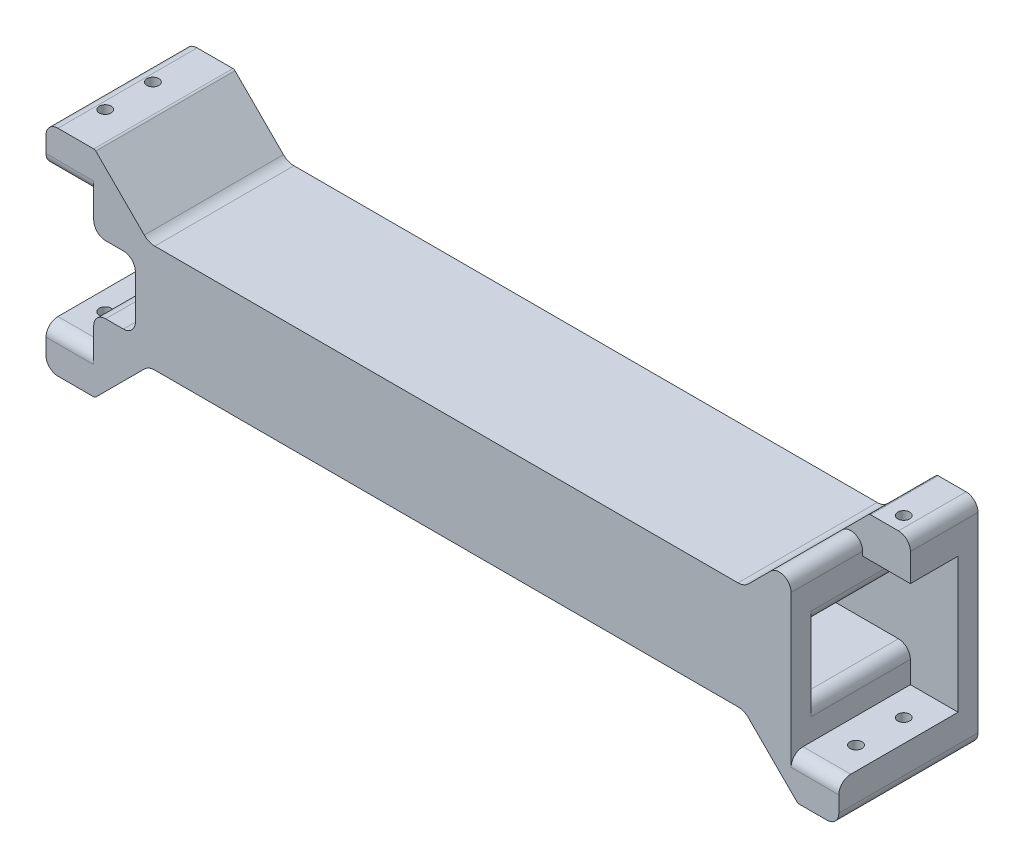
SolidWorks part; units mm, degrees
ref_plane "前视基准面" through (0, 0, 0) normal (0, 0, 1) x (1, 0, 0)
ref_plane "上视基准面" through (0, 0, 0) normal (0, 1, 0) x (1, 0, 0)
ref_plane "右视基准面" through (0, 0, 0) normal (1, 0, 0) x (0, 0, -1)
other "Configuration Table"
sketch "草图1" plane through (0, 0, 0) normal (0, 0, 1) x (1, 0, 0)
  line L0 (49.1217, 60) -> (0, 60) construction
  line L1 (0, 60) -> (0, 57) construction
  line L2 (0, 57) -> (49.1217, 57) construction
  line L3 (63.9537, 46.7157) -> (51.7639, 58.9056) construction
  line L4 (49.6425, 56.7843) -> (61.8324, 44.5944) construction
  line L5 (49.1217, 3) -> (0, 3) construction
  line L6 (0, 3) -> (0, 0) construction
  line L7 (0, 0) -> (49.1217, 0) construction
  line L8 (61.8324, 15.4056) -> (49.6425, 3.2157) construction
  line L9 (51.7639, 1.0944) -> (63.9537, 13.2843) construction
  line L10 (64.4745, 43.5) -> (211.1217, 43.5) construction
  line L11 (211.1217, 46.5) -> (64.4745, 46.5) construction
  line L12 (213.7639, 44.5944) -> (225.9537, 56.7843) construction
  line L13 (223.8324, 58.9056) -> (211.6425, 46.7157) construction
  line L14 (226.4745, 57) -> (269.9745, 57) construction
  line L15 (269.9745, 57) -> (269.9745, 60) construction
  line L16 (269.9745, 60) -> (226.4745, 60) construction
  line L17 (64.4745, 13.5) -> (211.1217, 13.5) construction
  line L18 (211.1217, 16.5) -> (64.4745, 16.5) construction
  line L19 (211.6425, 13.2843) -> (223.8324, 1.0944) construction
  line L20 (225.9537, 3.2157) -> (213.7639, 15.4056) construction
  line L21 (226.4745, 0) -> (269.9745, 0) construction
  line L22 (269.9745, 0) -> (269.9745, 3) construction
  line L23 (269.9745, 3) -> (226.4745, 3) construction
  line L24 (49.1217, 60) -> (0, 60)
  line L25 (0, 60) -> (0, 57)
  line L26 (0, 57) -> (49.1217, 57)
  line L27 (63.9537, 46.7157) -> (51.7639, 58.9056)
  line L28 (49.6425, 56.7843) -> (61.8324, 44.5944)
  line L29 (49.1217, 3) -> (0, 3)
  line L30 (0, 3) -> (0, 0)
  line L31 (0, 0) -> (49.1217, 0)
  line L32 (61.8324, 15.4056) -> (49.6425, 3.2157)
  line L33 (51.7639, 1.0944) -> (63.9537, 13.2843)
  line L34 (64.4745, 43.5) -> (211.1217, 43.5)
  line L35 (211.1217, 46.5) -> (64.4745, 46.5)
  line L36 (213.7639, 44.5944) -> (225.9537, 56.7843)
  line L37 (223.8324, 58.9056) -> (211.6425, 46.7157)
  line L38 (226.4745, 57) -> (269.9745, 57)
  line L39 (269.9745, 57) -> (269.9745, 60)
  line L40 (269.9745, 60) -> (226.4745, 60)
  line L41 (64.4745, 13.5) -> (211.1217, 13.5)
  line L42 (211.1217, 16.5) -> (64.4745, 16.5)
  line L43 (211.6425, 13.2843) -> (223.8324, 1.0944)
  line L44 (225.9537, 3.2157) -> (213.7639, 15.4056)
  line L45 (226.4745, 0) -> (269.9745, 0)
  line L46 (269.9745, 0) -> (269.9745, 3)
  line L47 (269.9745, 3) -> (226.4745, 3)
  line L48 (236.4745, 3) -> (236.4745, 57)
  line L49 (37.1217, 3) -> (37.1217, 57)
  arc A0 (49.6425, 56.7843) -> (49.1217, 57) centre (49.1217, 56.2634) ccw construction
  arc A1 (51.7639, 58.9056) -> (49.1217, 60) centre (49.1217, 56.2634) ccw construction
  arc A2 (61.8324, 44.5944) -> (64.4745, 43.5) centre (64.4745, 47.2366) ccw construction
  arc A3 (63.9537, 46.7157) -> (64.4745, 46.5) centre (64.4745, 47.2366) ccw construction
  arc A4 (49.1217, 0) -> (51.7639, 1.0944) centre (49.1217, 3.7366) ccw construction
  arc A5 (49.1217, 3) -> (49.6425, 3.2157) centre (49.1217, 3.7366) ccw construction
  arc A6 (64.4745, 13.5) -> (63.9537, 13.2843) centre (64.4745, 12.7634) ccw construction
  arc A7 (64.4745, 16.5) -> (61.8324, 15.4056) centre (64.4745, 12.7634) ccw construction
  arc A8 (211.1217, 43.5) -> (213.7639, 44.5944) centre (211.1217, 47.2366) ccw construction
  arc A9 (211.1217, 46.5) -> (211.6425, 46.7157) centre (211.1217, 47.2366) ccw construction
  arc A10 (226.4745, 57) -> (225.9537, 56.7843) centre (226.4745, 56.2634) ccw construction
  arc A11 (226.4745, 60) -> (223.8324, 58.9056) centre (226.4745, 56.2634) ccw construction
  arc A12 (211.6425, 13.2843) -> (211.1217, 13.5) centre (211.1217, 12.7634) ccw construction
  arc A13 (213.7639, 15.4056) -> (211.1217, 16.5) centre (211.1217, 12.7634) ccw construction
  arc A14 (223.8324, 1.0944) -> (226.4745, 0) centre (226.4745, 3.7366) ccw construction
  arc A15 (225.9537, 3.2157) -> (226.4745, 3) centre (226.4745, 3.7366) ccw construction
  arc A16 (49.6425, 56.7843) -> (49.1217, 57) centre (49.1217, 56.2634) ccw
  arc A17 (51.7639, 58.9056) -> (49.1217, 60) centre (49.1217, 56.2634) ccw
  arc A18 (61.8324, 44.5944) -> (64.4745, 43.5) centre (64.4745, 47.2366) ccw
  arc A19 (63.9537, 46.7157) -> (64.4745, 46.5) centre (64.4745, 47.2366) ccw
  arc A20 (49.1217, 0) -> (51.7639, 1.0944) centre (49.1217, 3.7366) ccw
  arc A21 (49.1217, 3) -> (49.6425, 3.2157) centre (49.1217, 3.7366) ccw
  arc A22 (64.4745, 13.5) -> (63.9537, 13.2843) centre (64.4745, 12.7634) ccw
  arc A23 (64.4745, 16.5) -> (61.8324, 15.4056) centre (64.4745, 12.7634) ccw
  arc A24 (211.1217, 43.5) -> (213.7639, 44.5944) centre (211.1217, 47.2366) ccw
  arc A25 (211.1217, 46.5) -> (211.6425, 46.7157) centre (211.1217, 47.2366) ccw
  arc A26 (226.4745, 57) -> (225.9537, 56.7843) centre (226.4745, 56.2634) ccw
  arc A27 (226.4745, 60) -> (223.8324, 58.9056) centre (226.4745, 56.2634) ccw
  arc A28 (211.6425, 13.2843) -> (211.1217, 13.5) centre (211.1217, 12.7634) ccw
  arc A29 (213.7639, 15.4056) -> (211.1217, 16.5) centre (211.1217, 12.7634) ccw
  arc A30 (223.8324, 1.0944) -> (226.4745, 0) centre (226.4745, 3.7366) ccw
  arc A31 (225.9537, 3.2157) -> (226.4745, 3) centre (226.4745, 3.7366) ccw
  dimension "D1" = 10
  dimension "D2" = 12
extrude "凸台-拉伸1" add sketch "草图1" against normal blind 35 contours L44 A31 L47 L48 L38 A26 L36 A24 L34 A18 L28 A16 L26 L49 L29 A21 L32 A23 L42 A29
sketch "草图2" plane through (37.1217, 0, 0) normal (-1, 0, 0) x (0, 0, 1)
  line L0 (-35, 43.5) -> (0, 43.5) construction
  line L1 (-35, 43.5) -> (0, 43.5)
  line L2 (-35, 16.5) -> (0, 16.5) construction
  line L3 (-35, 16.5) -> (0, 16.5)
  line L4 (-35, 43.5) -> (0, 16.5) construction
  line L5 (-35, 16.5) -> (0, 43.5) construction
  line L6 (0, 3) -> (0, 57) construction
  line L7 (-30, 38.5) -> (-5, 38.5)
  line L8 (-30, 38.5) -> (-30, 21.5)
  line L9 (-30, 21.5) -> (-5, 21.5)
  line L10 (-5, 38.5) -> (-5, 21.5)
  line L11 (-30, 38.5) -> (-5, 21.5) construction
  line L12 (-30, 21.5) -> (-5, 38.5) construction
  point P4 (-17.5, 30)
  dimension "D1" = 5
  dimension "D2" = 5
extrude "切除-拉伸1" cut sketch "草图2" against normal through all contours L10 L7 L8 L9
sketch "草图3" plane through (37.1217, 0, 0) normal (-1, 0, 0) x (0, 0, 1)
  line L0 (-30, 52) -> (-30, 8)
  line L1 (-30, 8) -> (-5, 8)
  line L2 (-5, 8) -> (-5, 52)
  line L3 (-5, 52) -> (-30, 52)
  line L4 (0, 3) -> (0, 57)
  line L5 (0, 57) -> (-35, 57)
  line L6 (-35, 57) -> (-35, 3)
  line L7 (-35, 3) -> (0, 3)
  line L8 (0, 3) -> (0, 57)
  line L9 (0, 57) -> (-35, 57)
  line L10 (-35, 57) -> (-35, 3)
  line L11 (-35, 3) -> (0, 3)
  line L12 (-30, 47) -> (-5, 47)
  line L13 (-30, 13) -> (-5, 13)
  line M14 (-5, 21.5) -> (-30, 21.5)
  line M16 (-30, 38.5) -> (-5, 38.5)
  dimension "D3" = 5
  dimension "D4" = 5
  dimension "D1" = 0
  dimension "D2" = 5
extrude "切除-拉伸2" cut sketch "草图3" against normal blind 12 contours L12 L0 L2 M16 | L0 L13 L2 M14
ref_plane "基准面1" through (136.7981, 0, 0) normal (-1, 0, 0) x (0, 0, 1)
mirror "镜向1" about plane through (136.7981, 0, 0) normal (-1, 0, 0) of "切除-拉伸2"
fillet "圆角1" radius 3 8 edges at (224.4745, 38.5, -17.5) (224.4745, 21.5, -17.5) (236.4745, 57, -17.5) (236.4745, 3, -17.5) (37.1217, 57, -17.5) (37.1217, 3, -17.5) (49.1217, 21.5, -17.5) (49.1217, 38.5, -17.5)
sketch "草图4" plane through (0, 57, 0) normal (0, 1, 0) x (1, 0, 0)
  circle A2 centre (42, 22) radius 1.5 construction
  circle A3 centre (42, 10) radius 1.5 construction
  circle A6 centre (42, 22) radius 1.5
  circle A7 centre (42, 10) radius 1.5
  circle A8 centre (230.7981, 22) radius 1.5 construction
  circle A9 centre (230.7981, 10) radius 1.5 construction
  circle A10 centre (230.7981, 22) radius 1.5
  circle A11 centre (230.7981, 10) radius 1.5
extrude "切除-拉伸3" cut sketch "草图4" against normal through all both and the other way through all
sketch "草图5" plane through (0, 0, -5) normal (0, 0, -1) x (-1, 0, 0)
  line L0 (-224.4745, 41.5) -> (-224.4745, 18.5)
  line L1 (-49.1217, 41.5) -> (-49.1217, 18.5)
  line L12 (-37.1217, 13) -> (-37.1217, 47)
  line L13 (-37.1217, 47) -> (-49.1217, 47)
  line L14 (-49.1217, 47) -> (-49.1217, 41.5)
  line L15 (-52.1217, 38.5) -> (-221.4745, 38.5)
  line L16 (-224.4745, 41.5) -> (-224.4745, 47)
  line L17 (-224.4745, 47) -> (-236.4745, 47)
  line L18 (-236.4745, 47) -> (-236.4745, 13)
  line L19 (-236.4745, 13) -> (-224.4745, 13)
  line L20 (-224.4745, 13) -> (-224.4745, 18.5)
  line L21 (-221.4745, 21.5) -> (-52.1217, 21.5)
  line L22 (-49.1217, 18.5) -> (-49.1217, 13)
  line L23 (-49.1217, 13) -> (-37.1217, 13)
  line L24 (-37.1217, 13) -> (-37.1217, 47)
  line L25 (-37.1217, 47) -> (-49.1217, 47)
  line L26 (-49.1217, 47) -> (-49.1217, 41.5)
  line L27 (-52.1217, 38.5) -> (-221.4745, 38.5)
  line L28 (-224.4745, 41.5) -> (-224.4745, 47)
  line L29 (-224.4745, 47) -> (-236.4745, 47)
  line L30 (-236.4745, 47) -> (-236.4745, 13)
  line L31 (-236.4745, 13) -> (-224.4745, 13)
  line L32 (-224.4745, 13) -> (-224.4745, 18.5)
  line L33 (-221.4745, 21.5) -> (-52.1217, 21.5)
  line L34 (-49.1217, 18.5) -> (-49.1217, 13)
  line L35 (-49.1217, 13) -> (-37.1217, 13)
  arc A4 (-52.1217, 38.5) -> (-49.1217, 41.5) centre (-52.1217, 41.5) ccw
  arc A5 (-224.4745, 41.5) -> (-221.4745, 38.5) centre (-221.4745, 41.5) ccw
  arc A6 (-221.4745, 21.5) -> (-224.4745, 18.5) centre (-221.4745, 18.5) ccw
  arc A7 (-49.1217, 18.5) -> (-52.1217, 21.5) centre (-52.1217, 18.5) ccw
  arc A8 (-52.1217, 38.5) -> (-49.1217, 41.5) centre (-52.1217, 41.5) ccw
  arc A9 (-224.4745, 41.5) -> (-221.4745, 38.5) centre (-221.4745, 41.5) ccw
  arc A10 (-221.4745, 21.5) -> (-224.4745, 18.5) centre (-221.4745, 18.5) ccw
  arc A11 (-49.1217, 18.5) -> (-52.1217, 21.5) centre (-52.1217, 18.5) ccw
  line M17 (-37.1217, 13) -> (-37.1217, 47)
  line M18 (-37.1217, 47) -> (-49.1217, 47)
  line M19 (-49.1217, 47) -> (-49.1217, 41.5)
  line M23 (-224.4745, 41.5) -> (-224.4745, 47)
  line M24 (-224.4745, 47) -> (-236.4745, 47)
  line M25 (-236.4745, 47) -> (-236.4745, 13)
  line M26 (-236.4745, 13) -> (-224.4745, 13)
  line M27 (-224.4745, 13) -> (-224.4745, 18.5)
  line M31 (-49.1217, 18.5) -> (-49.1217, 13)
  line M32 (-49.1217, 13) -> (-37.1217, 13)
  dimension "D1" = 0
extrude "切除-拉伸4" cut sketch "草图5" against normal blind 10 contours L0 M23 M24 M25 M26 M27 | L1 M19 M31 M32 M17 M18
fillet "圆角2" radius 3 4 edges at (230.4745, 13, 0) (230.4745, 47, 0) (43.1217, 13, 0) (43.1217, 47, 0)
sketch "草图6" plane through (0, 16.5, 0) normal (0, -1, 0) x (1, 0, 0)
  line L0 (106.7981, -17.5) -> (166.7981, -17.5) construction
  line L1 (136.7981, 19.25) -> (136.7981, -19.25) construction
  line L2 (106.7981, -9.5) -> (166.7981, -9.5)
  line L3 (106.7981, -25.5) -> (166.7981, -25.5)
  line L4 (136.7981, 0) -> (136.7981, -35)
  line L5 (211.1217, 0) -> (64.4745, 0) construction
  line L6 (211.1217, -35) -> (64.4745, -35) construction
  arc A0 (106.7981, -9.5) -> (106.7981, -25.5) centre (106.7981, -17.5) ccw
  arc A1 (166.7981, -25.5) -> (166.7981, -9.5) centre (166.7981, -17.5) ccw
  point P4 (136.7981, -17.5)
  dimension "D2" = 8
  dimension "D1" = 60
extrude "切除-拉伸5" [suppressed] cut sketch "草图6" against normal through all
sketch "草图7" plane through (0, 0, 0) normal (0, 0, 1) x (1, 0, 0)
  line L0 (236.4745, 47) -> (236.4745, 50) construction
  line L1 (224.4745, 47) -> (224.4745, 50) construction
  line L2 (224.4745, 47) -> (236.4745, 47) construction
  line L3 (49.1217, 50) -> (49.1217, 10) construction
  line L4 (49.1217, 10) -> (37.1217, 10) construction
  line L5 (37.1217, 10) -> (37.1217, 6) construction
  line L6 (40.1217, 3) -> (49.1217, 3) construction
  line L7 (49.6425, 3.2157) -> (61.8324, 15.4056) construction
  line L8 (64.4745, 16.5) -> (211.1217, 16.5) construction
  line L9 (213.7639, 15.4056) -> (225.9537, 3.2157) construction
  line L10 (226.4745, 3) -> (233.4745, 3) construction
  line L11 (236.4745, 6) -> (236.4745, 10) construction
  line L12 (236.4745, 10) -> (224.4745, 10) construction
  line L13 (224.4745, 10) -> (224.4745, 50) construction
  line L14 (236.4745, 50) -> (236.4745, 54) construction
  line L15 (233.4745, 57) -> (226.4745, 57) construction
  line L16 (225.9537, 56.7843) -> (213.7639, 44.5944) construction
  line L17 (211.1217, 43.5) -> (64.4745, 43.5) construction
  line L18 (61.8324, 44.5944) -> (49.6425, 56.7843) construction
  line L19 (49.1217, 57) -> (40.1217, 57) construction
  line L20 (37.1217, 54) -> (37.1217, 50) construction
  line L21 (37.1217, 50) -> (49.1217, 50) construction
  line L22 (236.4745, 47) -> (236.4745, 50)
  line L23 (224.4745, 47) -> (224.4745, 50)
  line L24 (224.4745, 47) -> (236.4745, 47)
  line L25 (49.1217, 50) -> (49.1217, 10)
  line L26 (49.1217, 10) -> (37.1217, 10)
  line L27 (37.1217, 10) -> (37.1217, 6)
  line L28 (40.1217, 3) -> (49.1217, 3)
  line L29 (49.6425, 3.2157) -> (61.8324, 15.4056)
  line L30 (64.4745, 16.5) -> (211.1217, 16.5)
  line L31 (213.7639, 15.4056) -> (225.9537, 3.2157)
  line L32 (226.4745, 3) -> (233.4745, 3)
  line L33 (236.4745, 6) -> (236.4745, 10)
  line L34 (236.4745, 10) -> (224.4745, 10)
  line L35 (224.4745, 10) -> (224.4745, 50)
  line L36 (236.4745, 50) -> (236.4745, 54)
  line L37 (233.4745, 57) -> (226.4745, 57)
  line L38 (225.9537, 56.7843) -> (213.7639, 44.5944)
  line L39 (211.1217, 43.5) -> (64.4745, 43.5)
  line L40 (61.8324, 44.5944) -> (49.6425, 56.7843)
  line L41 (49.1217, 57) -> (40.1217, 57)
  line L42 (37.1217, 54) -> (37.1217, 50)
  line L43 (37.1217, 50) -> (49.1217, 50)
  line L44 (224.4745, 50) -> (224.4745, 55.3051)
  arc A0 (37.1217, 6) -> (40.1217, 3) centre (40.1217, 6) ccw construction
  arc A1 (49.1217, 3) -> (49.6425, 3.2157) centre (49.1217, 3.7366) ccw construction
  arc A2 (64.4745, 16.5) -> (61.8324, 15.4056) centre (64.4745, 12.7634) ccw construction
  arc A3 (213.7639, 15.4056) -> (211.1217, 16.5) centre (211.1217, 12.7634) ccw construction
  arc A4 (225.9537, 3.2157) -> (226.4745, 3) centre (226.4745, 3.7366) ccw construction
  arc A5 (233.4745, 3) -> (236.4745, 6) centre (233.4745, 6) ccw construction
  arc A6 (236.4745, 54) -> (233.4745, 57) centre (233.4745, 54) ccw construction
  arc A7 (226.4745, 57) -> (225.9537, 56.7843) centre (226.4745, 56.2634) ccw construction
  arc A8 (211.1217, 43.5) -> (213.7639, 44.5944) centre (211.1217, 47.2366) ccw construction
  arc A9 (61.8324, 44.5944) -> (64.4745, 43.5) centre (64.4745, 47.2366) ccw construction
  arc A10 (49.6425, 56.7843) -> (49.1217, 57) centre (49.1217, 56.2634) ccw construction
  arc A11 (40.1217, 57) -> (37.1217, 54) centre (40.1217, 54) ccw construction
  arc A12 (37.1217, 6) -> (40.1217, 3) centre (40.1217, 6) ccw
  arc A13 (49.1217, 3) -> (49.6425, 3.2157) centre (49.1217, 3.7366) ccw
  arc A14 (64.4745, 16.5) -> (61.8324, 15.4056) centre (64.4745, 12.7634) ccw
  arc A15 (213.7639, 15.4056) -> (211.1217, 16.5) centre (211.1217, 12.7634) ccw
  arc A16 (225.9537, 3.2157) -> (226.4745, 3) centre (226.4745, 3.7366) ccw
  arc A17 (233.4745, 3) -> (236.4745, 6) centre (233.4745, 6) ccw
  arc A18 (236.4745, 54) -> (233.4745, 57) centre (233.4745, 54) ccw
  arc A19 (226.4745, 57) -> (225.9537, 56.7843) centre (226.4745, 56.2634) ccw
  arc A20 (211.1217, 43.5) -> (213.7639, 44.5944) centre (211.1217, 47.2366) ccw
  arc A21 (61.8324, 44.5944) -> (64.4745, 43.5) centre (64.4745, 47.2366) ccw
  arc A22 (49.6425, 56.7843) -> (49.1217, 57) centre (49.1217, 56.2634) ccw
  arc A23 (40.1217, 57) -> (37.1217, 54) centre (40.1217, 54) ccw
  line M17 (224.4745, 10) -> (224.4745, 50)
  line M18 (224.4745, 50) -> (236.4745, 50)
  line M19 (236.4745, 50) -> (236.4745, 54)
  arc M20 (236.4745, 54) -> (233.4745, 57) centre (233.4745, 54) ccw
  line M21 (233.4745, 57) -> (226.4745, 57)
  arc M22 (226.4745, 57) -> (225.9537, 56.7843) centre (226.4745, 56.2634) ccw
  line M23 (225.9537, 56.7843) -> (213.7639, 44.5944)
extrude "切除-拉伸6" cut sketch "草图7" against normal blind 18 contours L24 L22 M17 M18 | L44 M18 M19 M20 M21 M22 M23
fillet "圆角3" radius 3 1 edges at (224.4745, 55.3051, -9)
sketch "草图8" plane through (0, 0, -30) normal (0, 0, 1) x (1, 0, 0)
  line L0 (224.4745, 41.5) -> (224.4745, 18.5)
  line L1 (49.1217, 41.5) -> (49.1217, 18.5)
  line L12 (37.1217, 47) -> (37.1217, 13)
  line L13 (37.1217, 13) -> (49.1217, 13)
  line L14 (49.1217, 13) -> (49.1217, 18.5)
  line L15 (52.1217, 21.5) -> (221.4745, 21.5)
  line L16 (224.4745, 18.5) -> (224.4745, 13)
  line L17 (224.4745, 13) -> (236.4745, 13)
  line L18 (236.4745, 13) -> (236.4745, 47)
  line L19 (236.4745, 47) -> (224.4745, 47)
  line L20 (224.4745, 47) -> (224.4745, 41.5)
  line L21 (221.4745, 38.5) -> (52.1217, 38.5)
  line L22 (49.1217, 41.5) -> (49.1217, 47)
  line L23 (49.1217, 47) -> (37.1217, 47)
  line L24 (37.1217, 47) -> (37.1217, 13)
  line L25 (37.1217, 13) -> (49.1217, 13)
  line L26 (49.1217, 13) -> (49.1217, 18.5)
  line L27 (52.1217, 21.5) -> (221.4745, 21.5)
  line L28 (224.4745, 18.5) -> (224.4745, 13)
  line L29 (224.4745, 13) -> (236.4745, 13)
  line L30 (236.4745, 13) -> (236.4745, 47)
  line L31 (236.4745, 47) -> (224.4745, 47)
  line L32 (224.4745, 47) -> (224.4745, 41.5)
  line L33 (221.4745, 38.5) -> (52.1217, 38.5)
  line L34 (49.1217, 41.5) -> (49.1217, 47)
  line L35 (49.1217, 47) -> (37.1217, 47)
  arc A4 (52.1217, 21.5) -> (49.1217, 18.5) centre (52.1217, 18.5) ccw
  arc A5 (224.4745, 18.5) -> (221.4745, 21.5) centre (221.4745, 18.5) ccw
  arc A6 (221.4745, 38.5) -> (224.4745, 41.5) centre (221.4745, 41.5) ccw
  arc A7 (49.1217, 41.5) -> (52.1217, 38.5) centre (52.1217, 41.5) ccw
  arc A8 (52.1217, 21.5) -> (49.1217, 18.5) centre (52.1217, 18.5) ccw
  arc A9 (224.4745, 18.5) -> (221.4745, 21.5) centre (221.4745, 18.5) ccw
  arc A10 (221.4745, 38.5) -> (224.4745, 41.5) centre (221.4745, 41.5) ccw
  arc A11 (49.1217, 41.5) -> (52.1217, 38.5) centre (52.1217, 41.5) ccw
  line M17 (37.1217, 47) -> (37.1217, 13)
  line M18 (37.1217, 13) -> (49.1217, 13)
  line M19 (49.1217, 13) -> (49.1217, 18.5)
  line M31 (49.1217, 41.5) -> (49.1217, 47)
  line M32 (49.1217, 47) -> (37.1217, 47)
  dimension "D1" = 0
extrude "切除-拉伸8" cut sketch "草图8" against normal blind 10 contours L1 M31 M32 M17 M18 M19
fillet "圆角4" radius 3 2 edges at (43.1217, 13, -35) (43.1217, 47, -35)
sketch "草图9" plane through (0, 0, -35) normal (0, 0, -1) x (-1, 0, 0)
  circle A0 centre (-55.1912, 25) radius 1.5 construction
  circle A1 centre (-55.1912, 25) radius 1.5
  circle A2 centre (-55.1912, 35) radius 1.5 construction
  circle A3 centre (-55.1912, 35) radius 1.5
extrude "切除-拉伸9" cut sketch "草图9" against normal blind 8
sketch "草图10" plane through (0, 0, -5) normal (0, 0, -1) x (-1, 0, 0)
  line L0 (-59.5869, 38.5) -> (-59.5869, 21.5)
  line L4 (-224.4745, 41.5) -> (-224.4745, 18.5)
  line L5 (-221.4745, 21.5) -> (-52.1217, 21.5)
  line L6 (-49.1217, 18.5) -> (-49.1217, 41.5)
  line L7 (-52.1217, 38.5) -> (-221.4745, 38.5)
  line L8 (-224.4745, 41.5) -> (-224.4745, 18.5)
  line L9 (-221.4745, 21.5) -> (-52.1217, 21.5)
  line L10 (-49.1217, 18.5) -> (-49.1217, 41.5)
  line L11 (-52.1217, 38.5) -> (-221.4745, 38.5)
  arc A4 (-224.4745, 41.5) -> (-221.4745, 38.5) centre (-221.4745, 41.5) ccw
  arc A5 (-221.4745, 21.5) -> (-224.4745, 18.5) centre (-221.4745, 18.5) ccw
  arc A6 (-49.1217, 18.5) -> (-52.1217, 21.5) centre (-52.1217, 18.5) ccw
  arc A7 (-52.1217, 38.5) -> (-49.1217, 41.5) centre (-52.1217, 41.5) ccw
  arc A8 (-224.4745, 41.5) -> (-221.4745, 38.5) centre (-221.4745, 41.5) ccw
  arc A9 (-221.4745, 21.5) -> (-224.4745, 18.5) centre (-221.4745, 18.5) ccw
  arc A10 (-49.1217, 18.5) -> (-52.1217, 21.5) centre (-52.1217, 18.5) ccw
  arc A11 (-52.1217, 38.5) -> (-49.1217, 41.5) centre (-52.1217, 41.5) ccw
  line M12 (-221.4745, 21.5) -> (-52.1217, 21.5)
  arc M13 (-52.1217, 21.5) -> (-49.1217, 18.5) centre (-52.1217, 18.5) cw
  line M14 (-49.1217, 18.5) -> (-49.1217, 41.5)
  arc M15 (-49.1217, 41.5) -> (-52.1217, 38.5) centre (-52.1217, 41.5) cw
  line M16 (-52.1217, 38.5) -> (-221.4745, 38.5)
  dimension "D1" = 0
extrude "切除-拉伸10" cut sketch "草图10" against normal blind 8 contours L0 M16 M12 M13 M14 M15
fillet "圆角5" radius 3 2 edges at (59.5869, 21.5, -2.5) (59.5869, 38.5, -2.5)
